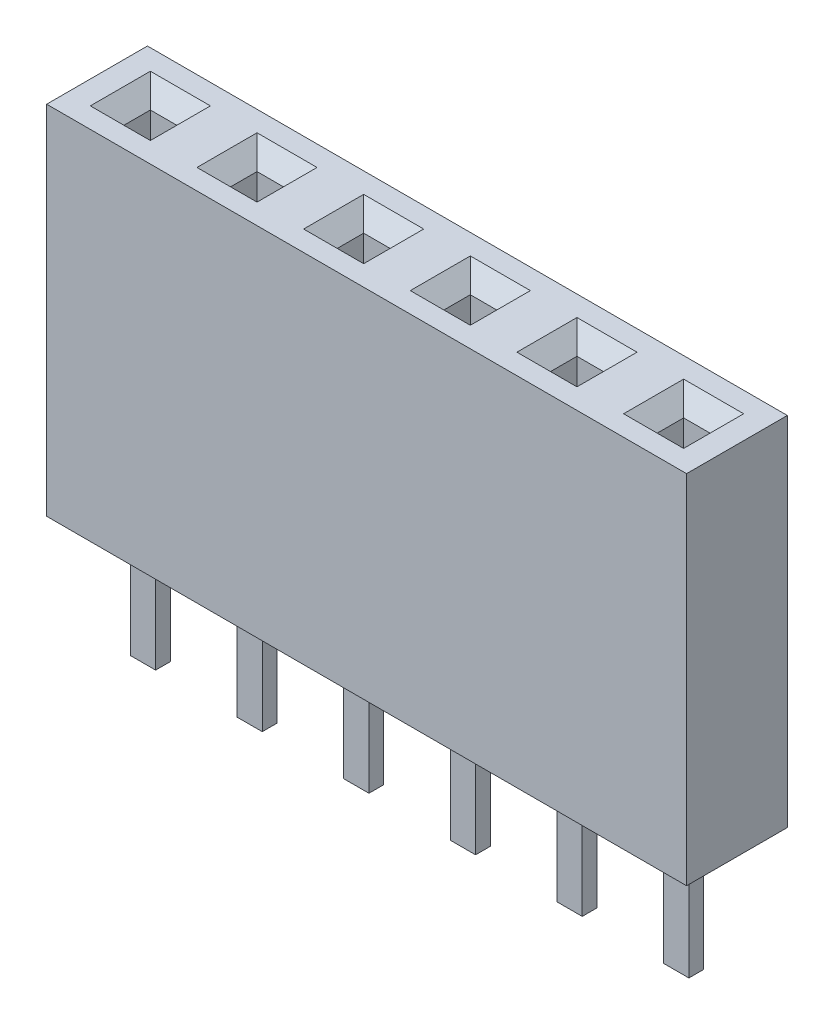
SolidWorks part; units mm, degrees
ref_plane "Front Plane" through (0, 0, 0) normal (0, 0, 1) x (1, 0, 0)
ref_plane "Top Plane" through (0, 0, 0) normal (0, 1, 0) x (1, 0, 0)
ref_plane "Right Plane" through (0, 0, 0) normal (1, 0, 0) x (0, 0, -1)
sketch "Sketch1" plane through (0, 0, 0) normal (0, 1, 0) x (1, 0, 0)
  line L1 (19.05, -1.2) -> (-19.05, -1.2)
  line L2 (19.05, -1.2) -> (19.05, 1.2)
  line L3 (19.05, 1.2) -> (-19.05, 1.2)
  line L4 (-19.05, -1.2) -> (-19.05, 1.2)
  line L5 (19.05, -1.2) -> (-19.05, 1.2) construction
  line L6 (19.05, 1.2) -> (-19.05, -1.2) construction
  point P0 (0, 0)
  dimension "D1" = 2.4
  dimension "D2" = 38.1
extrude "Boss-Extrude1" add sketch "Sketch1" along normal blind 8.5
sketch "Sketch2" plane through (0, 8.5, 0) normal (0, 1, 0) x (1, 0, 0)
  line L0 (-19.05, 0) -> (19.05, 0) construction
  line L1 (-19.05, 1.2) -> (-19.05, -1.2) construction
  line L2 (19.05, -1.2) -> (19.05, 1.2) construction
  line L3 (-15.555, 0.315) -> (-14.925, 0.315)
  line L4 (-18.095, -0.315) -> (-17.465, -0.315)
  line L5 (-18.095, -0.315) -> (-18.095, 0.315)
  line L6 (-18.095, 0.315) -> (-17.465, 0.315)
  line L7 (-17.465, -0.315) -> (-17.465, 0.315)
  line L8 (-18.095, -0.315) -> (-17.465, 0.315) construction
  line L9 (-18.095, 0.315) -> (-17.465, -0.315) construction
  line L10 (-15.555, -0.315) -> (-15.555, 0.315)
  line L11 (-15.555, -0.315) -> (-14.925, -0.315)
  line L12 (-14.925, -0.315) -> (-14.925, 0.315)
  line L13 (-13.015, 0.315) -> (-12.385, 0.315)
  line L14 (-13.015, -0.315) -> (-13.015, 0.315)
  line L15 (-13.015, -0.315) -> (-12.385, -0.315)
  line L16 (-12.385, -0.315) -> (-12.385, 0.315)
  line L17 (-10.475, 0.315) -> (-9.845, 0.315)
  line L18 (-10.475, -0.315) -> (-10.475, 0.315)
  line L19 (-10.475, -0.315) -> (-9.845, -0.315)
  line L20 (-9.845, -0.315) -> (-9.845, 0.315)
  line L21 (-7.935, 0.315) -> (-7.305, 0.315)
  line L22 (-7.935, -0.315) -> (-7.935, 0.315)
  line L23 (-7.935, -0.315) -> (-7.305, -0.315)
  line L24 (-7.305, -0.315) -> (-7.305, 0.315)
  line L25 (-5.395, 0.315) -> (-4.765, 0.315)
  line L26 (-5.395, -0.315) -> (-5.395, 0.315)
  line L27 (-5.395, -0.315) -> (-4.765, -0.315)
  line L28 (-4.765, -0.315) -> (-4.765, 0.315)
  line L29 (-2.855, 0.315) -> (-2.225, 0.315)
  line L30 (-2.855, -0.315) -> (-2.855, 0.315)
  line L31 (-2.855, -0.315) -> (-2.225, -0.315)
  line L32 (-2.225, -0.315) -> (-2.225, 0.315)
  line L33 (-0.315, 0.315) -> (0.315, 0.315)
  line L34 (-0.315, -0.315) -> (-0.315, 0.315)
  line L35 (-0.315, -0.315) -> (0.315, -0.315)
  line L36 (0.315, -0.315) -> (0.315, 0.315)
  line L37 (2.225, 0.315) -> (2.855, 0.315)
  line L38 (2.225, -0.315) -> (2.225, 0.315)
  line L39 (2.225, -0.315) -> (2.855, -0.315)
  line L40 (2.855, -0.315) -> (2.855, 0.315)
  line L41 (4.765, 0.315) -> (5.395, 0.315)
  line L42 (4.765, -0.315) -> (4.765, 0.315)
  line L43 (4.765, -0.315) -> (5.395, -0.315)
  line L44 (5.395, -0.315) -> (5.395, 0.315)
  line L45 (7.305, 0.315) -> (7.935, 0.315)
  line L46 (7.305, -0.315) -> (7.305, 0.315)
  line L47 (7.305, -0.315) -> (7.935, -0.315)
  line L48 (7.935, -0.315) -> (7.935, 0.315)
  line L49 (9.845, 0.315) -> (10.475, 0.315)
  line L50 (9.845, -0.315) -> (9.845, 0.315)
  line L51 (9.845, -0.315) -> (10.475, -0.315)
  line L52 (10.475, -0.315) -> (10.475, 0.315)
  line L53 (12.385, 0.315) -> (13.015, 0.315)
  line L54 (12.385, -0.315) -> (12.385, 0.315)
  line L55 (12.385, -0.315) -> (13.015, -0.315)
  line L56 (13.015, -0.315) -> (13.015, 0.315)
  line L57 (14.925, 0.315) -> (15.555, 0.315)
  line L58 (14.925, -0.315) -> (14.925, 0.315)
  line L59 (14.925, -0.315) -> (15.555, -0.315)
  line L60 (15.555, -0.315) -> (15.555, 0.315)
  line L61 (17.465, 0.315) -> (18.095, 0.315)
  line L62 (17.465, -0.315) -> (17.465, 0.315)
  line L63 (17.465, -0.315) -> (18.095, -0.315)
  line L64 (18.095, -0.315) -> (18.095, 0.315)
  point P6 (-17.78, 0)
  dimension "D1" = 0.63
  dimension "D2" = 0.63
  dimension "D3" = 1.27
  dimension "D4" = 15
extrude "Cut-Extrude1" cut sketch "Sketch2" against normal blind 6.5
sketch "Sketch3" plane through (0, 0, 0) normal (0, -1, 0) x (1, 0, 0)
  line L0 (-19.05, 0) -> (19.05, 0) construction
  line L1 (-19.05, -1.2) -> (-19.05, 1.2) construction
  line L2 (19.05, 1.2) -> (19.05, -1.2) construction
  line L3 (-15.54, 0.175) -> (-14.94, 0.175)
  line L4 (-18.08, -0.175) -> (-17.48, -0.175)
  line L5 (-18.08, -0.175) -> (-18.08, 0.175)
  line L6 (-18.08, 0.175) -> (-17.48, 0.175)
  line L7 (-17.48, -0.175) -> (-17.48, 0.175)
  line L8 (-18.08, -0.175) -> (-17.48, 0.175) construction
  line L9 (-18.08, 0.175) -> (-17.48, -0.175) construction
  line L10 (-15.54, -0.175) -> (-15.54, 0.175)
  line L11 (-15.54, -0.175) -> (-14.94, -0.175)
  line L12 (-14.94, -0.175) -> (-14.94, 0.175)
  line L13 (-13, 0.175) -> (-12.4, 0.175)
  line L14 (-13, -0.175) -> (-13, 0.175)
  line L15 (-13, -0.175) -> (-12.4, -0.175)
  line L16 (-12.4, -0.175) -> (-12.4, 0.175)
  line L17 (-10.46, 0.175) -> (-9.86, 0.175)
  line L18 (-10.46, -0.175) -> (-10.46, 0.175)
  line L19 (-10.46, -0.175) -> (-9.86, -0.175)
  line L20 (-9.86, -0.175) -> (-9.86, 0.175)
  line L21 (-7.92, 0.175) -> (-7.32, 0.175)
  line L22 (-7.92, -0.175) -> (-7.92, 0.175)
  line L23 (-7.92, -0.175) -> (-7.32, -0.175)
  line L24 (-7.32, -0.175) -> (-7.32, 0.175)
  line L25 (-5.38, 0.175) -> (-4.78, 0.175)
  line L26 (-5.38, -0.175) -> (-5.38, 0.175)
  line L27 (-5.38, -0.175) -> (-4.78, -0.175)
  line L28 (-4.78, -0.175) -> (-4.78, 0.175)
  line L29 (-2.84, 0.175) -> (-2.24, 0.175)
  line L30 (-2.84, -0.175) -> (-2.84, 0.175)
  line L31 (-2.84, -0.175) -> (-2.24, -0.175)
  line L32 (-2.24, -0.175) -> (-2.24, 0.175)
  line L33 (-0.3, 0.175) -> (0.3, 0.175)
  line L34 (-0.3, -0.175) -> (-0.3, 0.175)
  line L35 (-0.3, -0.175) -> (0.3, -0.175)
  line L36 (0.3, -0.175) -> (0.3, 0.175)
  line L37 (2.24, 0.175) -> (2.84, 0.175)
  line L38 (2.24, -0.175) -> (2.24, 0.175)
  line L39 (2.24, -0.175) -> (2.84, -0.175)
  line L40 (2.84, -0.175) -> (2.84, 0.175)
  line L41 (4.78, 0.175) -> (5.38, 0.175)
  line L42 (4.78, -0.175) -> (4.78, 0.175)
  line L43 (4.78, -0.175) -> (5.38, -0.175)
  line L44 (5.38, -0.175) -> (5.38, 0.175)
  line L45 (7.32, 0.175) -> (7.92, 0.175)
  line L46 (7.32, -0.175) -> (7.32, 0.175)
  line L47 (7.32, -0.175) -> (7.92, -0.175)
  line L48 (7.92, -0.175) -> (7.92, 0.175)
  line L49 (9.86, 0.175) -> (10.46, 0.175)
  line L50 (9.86, -0.175) -> (9.86, 0.175)
  line L51 (9.86, -0.175) -> (10.46, -0.175)
  line L52 (10.46, -0.175) -> (10.46, 0.175)
  line L53 (12.4, 0.175) -> (13, 0.175)
  line L54 (12.4, -0.175) -> (12.4, 0.175)
  line L55 (12.4, -0.175) -> (13, -0.175)
  line L56 (13, -0.175) -> (13, 0.175)
  line L57 (14.94, 0.175) -> (15.54, 0.175)
  line L58 (14.94, -0.175) -> (14.94, 0.175)
  line L59 (14.94, -0.175) -> (15.54, -0.175)
  line L60 (15.54, -0.175) -> (15.54, 0.175)
  line L61 (17.48, 0.175) -> (18.08, 0.175)
  line L62 (17.48, -0.175) -> (17.48, 0.175)
  line L63 (17.48, -0.175) -> (18.08, -0.175)
  line L64 (18.08, -0.175) -> (18.08, 0.175)
  point P6 (-17.78, 0)
  dimension "D1" = 0.35
  dimension "D2" = 0.6
  dimension "D3" = 1.27
  dimension "D4" = 15
extrude "Boss-Extrude2" add sketch "Sketch3" along normal blind 2.9
chamfer "Chamfer1" distance 0.4 angle 45 60 edges at (0, 8.5, 0.315) (0.315, 8.5, 0) (0, 8.5, -0.315) (-0.315, 8.5, 0) (-2.54, 8.5, 0.315) (-2.225, 8.5, 0) (-2.54, 8.5, -0.315) (-2.855, 8.5, 0) (-5.08, 8.5, 0.315) (-4.765, 8.5, 0) (-5.08, 8.5, -0.315) (-5.395, 8.5, 0) (-7.62, 8.5, 0.315) (-7.305, 8.5, 0) (-7.62, 8.5, -0.315) (-7.935, 8.5, 0) (-10.16, 8.5, 0.315) (-9.845, 8.5, 0) (-10.16, 8.5, -0.315) (-10.475, 8.5, 0) (-12.385, 8.5, 0) (-12.7, 8.5, -0.315) (-13.015, 8.5, 0) (-12.7, 8.5, 0.315) (-15.24, 8.5, 0.315) (-14.925, 8.5, 0) (-15.24, 8.5, -0.315) (-15.555, 8.5, 0) (-17.78, 8.5, 0.315) (-17.465, 8.5, 0) (-17.78, 8.5, -0.315) (-18.095, 8.5, 0) (17.78, 8.5, 0.315) (18.095, 8.5, 0) (17.78, 8.5, -0.315) (17.465, 8.5, 0) (15.24, 8.5, 0.315) (15.555, 8.5, 0) (15.24, 8.5, -0.315) (14.925, 8.5, 0) (12.385, 8.5, 0) (12.7, 8.5, 0.315) (13.015, 8.5, 0) (12.7, 8.5, -0.315) (9.845, 8.5, 0) (10.16, 8.5, 0.315) (10.475, 8.5, 0) (10.16, 8.5, -0.315) (7.305, 8.5, 0) (7.62, 8.5, 0.315) (7.935, 8.5, 0) (7.62, 8.5, -0.315) (4.765, 8.5, 0) (5.08, 8.5, 0.315) (5.395, 8.5, 0) (5.08, 8.5, -0.315) (2.225, 8.5, 0) (2.54, 8.5, -0.315) (2.855, 8.5, 0) (2.54, 8.5, 0.315)
sketch "Sketch4" plane through (0, 8.5, 0) normal (0, 1, 0) x (1, 0, 0)
  line L0 (5.395, 0) -> (7.305, 0) construction
  line L3 (6.35, 0) -> (6.35, 2.1388) construction
  line L4 (5.395, -0.315) -> (5.395, 0.315) construction
  line L5 (6.35, 2.1388) -> (25.7288, 2.1388)
  line L6 (6.35, 2.1388) -> (6.35, -2.3327)
  line L7 (6.35, -2.3327) -> (25.7288, -2.3327)
  line L8 (25.7288, 2.1388) -> (25.7288, -2.3327)
  line L9 (7.305, 0.315) -> (7.305, -0.315) construction
  point P11 (6.35, 0)
extrude "Cut-Extrude2" cut sketch "Sketch4" against normal through all
sketch "Sketch5" plane through (0, 0, 0) normal (0, -1, 0) x (-1, 0, 0)
  line L0 (17.78, -1.2) -> (17.78, 1.2) construction
  line L1 (19.05, -1.2) -> (-6.35, -1.2) construction
  line L2 (-6.35, 1.2) -> (19.05, 1.2) construction
  line L3 (18.08, 0) -> (17.48, 0) construction
  line L4 (18.08, -0.175) -> (18.08, 0.175) construction
  line L5 (17.48, 0.175) -> (17.48, -0.175) construction
  point P12 (17.78, 0)
sketch "Sketch6" plane through (0, 8.5, 0) normal (0, 1, 0) x (1, 0, 0)
  line L0 (-18.495, 0) -> (-17.065, 0) construction
  line L1 (-18.495, -0.715) -> (-18.495, 0.715) construction
  line L2 (-17.065, 0.715) -> (-17.065, -0.715) construction
  line L3 (4.365, 0) -> (5.795, 0) construction
  line L4 (4.365, -0.715) -> (4.365, 0.715) construction
  line L5 (5.795, 0.715) -> (5.795, -0.715) construction
  point P12 (-17.78, 0)
  point P13 (5.08, 0)
sketch "Sketch8" plane through (0, 0, 1.2) normal (0, 0, 1) x (1, 0, 0)
  line L1 (-19.05, 8.5) -> (-8.89, 8.5)
  line L2 (-19.05, 8.5) -> (-19.05, -4.6509)
  line L3 (-19.05, -4.6509) -> (-8.89, -4.6509)
  line L4 (-8.89, 8.5) -> (-8.89, -4.6509)
  dimension "D1" = 10.16
extrude "Cut-Extrude3" cut sketch "Sketch8" against normal through all
